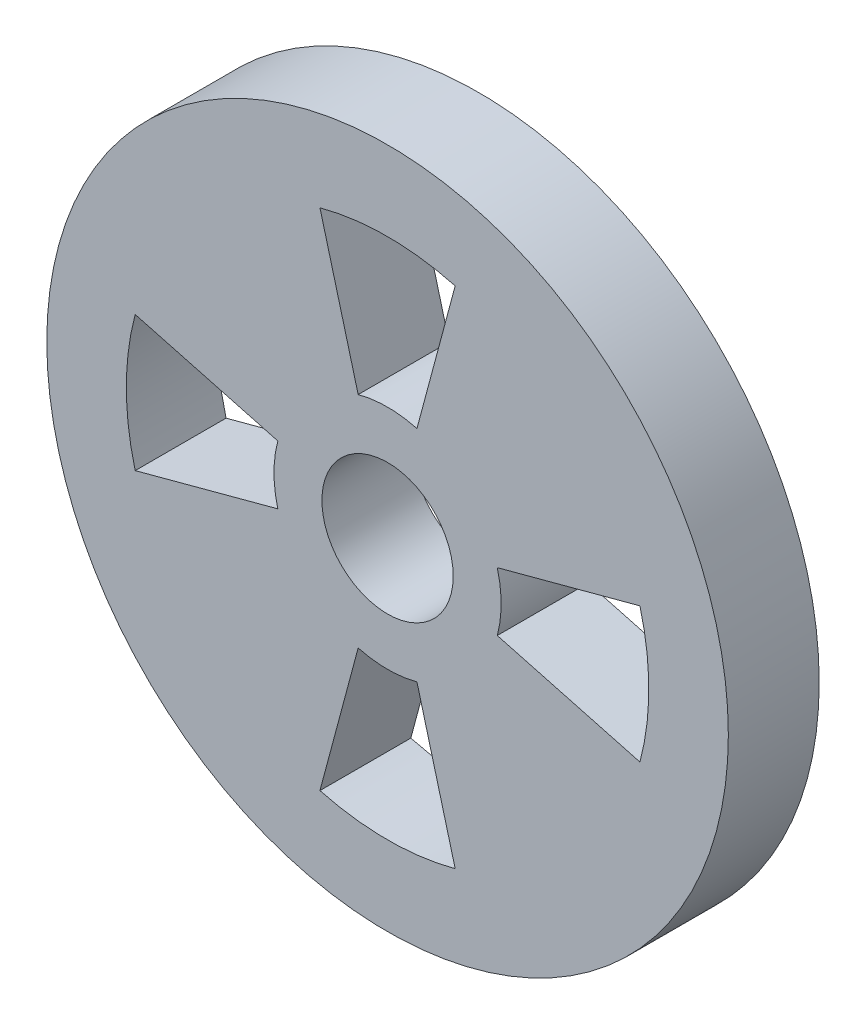
SolidWorks part; units mm, degrees
ref_plane "Piano frontale" through (0, 0, 0) normal (0, 0, 1) x (1, 0, 0)
ref_plane "Piano superiore" through (0, 0, 0) normal (0, 1, 0) x (1, 0, 0)
ref_plane "Piano destro" through (0, 0, 0) normal (1, 0, 0) x (0, 0, -1)
sketch "Schizzo1" plane through (0, 0, 0) normal (0, 0, 1) x (1, 0, 0)
  circle A0 centre (0, 0) radius 15
  circle A1 centre (0, 0) radius 2.89
  dimension "D1" = 30
  dimension "D2" = 5.78
extrude "Estrusione-Estrusione1" add sketch "Schizzo1" along normal blind 4
sketch "Schizzo2" plane through (0, 0, 4) normal (0, 0, 1) x (1, 0, 0)
  line L0 (0, 15) -> (0, -15) construction
  line L1 (-4.8296, -1.2941) -> (-11.1081, -2.9764)
  line L2 (15, 0) -> (-15, 0) construction
  line L3 (11.1081, -2.9764) -> (4.8296, -1.2941)
  line L4 (-4.8296, 1.2941) -> (-11.1081, 2.9764)
  line L5 (-2.9764, 11.1081) -> (-1.2941, 4.8296)
  line L6 (1.2941, 4.8296) -> (2.9764, 11.1081)
  line L7 (-2.9764, -11.1081) -> (-1.2941, -4.8296)
  line L8 (1.2941, -4.8296) -> (2.9764, -11.1081)
  line L9 (11.1081, 2.9764) -> (4.8296, 1.2941)
  arc A0 (-4.8296, 1.2941) -> (-4.8296, -1.2941) centre (0, 0) ccw
  arc A1 (-11.1081, 2.9764) -> (-11.1081, -2.9764) centre (0, 0) ccw
  circle A2 centre (0, 0) radius 15 construction
  arc A3 (-1.2941, -4.8296) -> (1.2941, -4.8296) centre (0, 0) ccw
  arc A4 (-2.9764, -11.1081) -> (2.9764, -11.1081) centre (0, 0) ccw
  arc A5 (11.1081, -2.9764) -> (11.1081, 2.9764) centre (0, 0) ccw
  arc A6 (4.8296, -1.2941) -> (4.8296, 1.2941) centre (0, 0) ccw
  arc A7 (1.2941, 4.8296) -> (-1.2941, 4.8296) centre (0, 0) ccw
  arc A8 (2.9764, 11.1081) -> (-2.9764, 11.1081) centre (0, 0) ccw
  dimension "D1" = 10
  dimension "D2" = 6.5
  dimension "D3" = 30
  dimension "D4" = 15
  dimension "D5" = 30
  dimension "D6" = 15
extrude "Taglio-Estrusione1" cut sketch "Schizzo2" against normal through all
